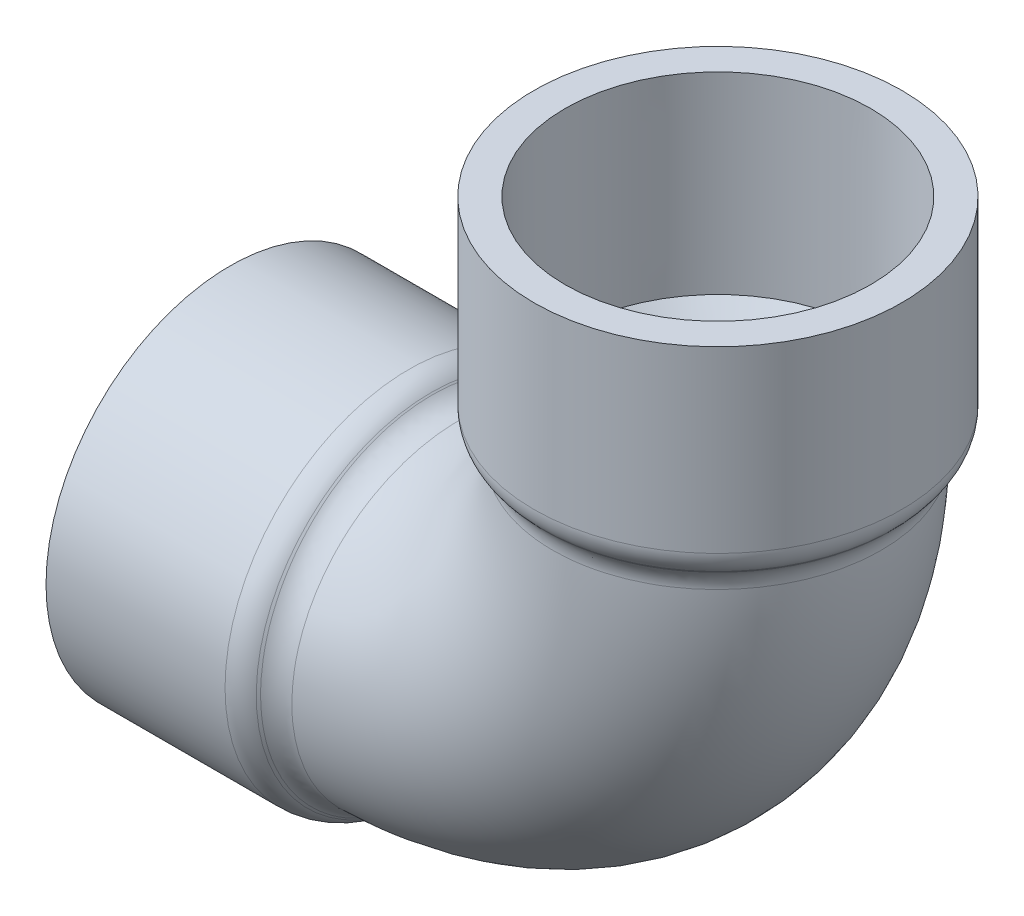
SolidWorks part; units mm, degrees
ref_plane "Front Plane" through (0, 0, 0) normal (0, 0, 1) x (1, 0, 0)
ref_plane "Top Plane" through (0, 0, 0) normal (0, 1, 0) x (1, 0, 0)
ref_plane "Right Plane" through (0, 0, 0) normal (1, 0, 0) x (0, 0, -1)
sketch "Sketch0" plane through (0, 0, 0) normal (0, 0, 1) x (1, 0, 0)
  line L0 (-96.8375, 0) -> (0, 0) construction
  line L1 (0, 0) -> (0, 96.8375) construction
  line L2 (-58.7375, 0) -> (0, 0) construction
  line L3 (0, 0) -> (0, 58.7375) construction
  line L4 (-96.8375, 36.5125) -> (-96.8375, -36.5125) construction
  line L5 (-58.7375, 30.0863) -> (-96.8375, 30.3149) construction
  line L6 (-58.7375, 30.0863) -> (-58.7375, -30.0863) construction
  line L7 (-58.7375, -30.0863) -> (-96.8375, -30.3149) construction
  line L8 (-96.8375, 30.3149) -> (-96.8375, -30.3149) construction
  line L9 (-36.5125, 96.8375) -> (36.5125, 96.8375) construction
  line L10 (-30.3149, 96.8375) -> (30.3149, 96.8375) construction
  line L11 (30.3149, 96.8375) -> (30.0863, 58.7375) construction
  line L12 (30.0863, 58.7375) -> (-30.0863, 58.7375) construction
  line L13 (-30.0863, 58.7375) -> (-30.3149, 96.8375) construction
  line L14 (-58.7375, 26.2509) -> (-58.7375, -26.2509) construction
  line L15 (-58.7375, -26.2509) -> (-58.7375, -32.4485) construction
  line L16 (-96.8375, -30.3149) -> (-96.8375, -36.5125) construction
  line L17 (26.2509, 58.7375) -> (32.4485, 58.7375) construction
  line L18 (-26.2509, 58.7375) -> (26.2509, 58.7375) construction
  line L19 (30.3149, 96.8375) -> (36.5125, 96.8375) construction
  dimension "D1" = 6.1976
  dimension "H" = 96.8375
  dimension "G" = 58.7375
  dimension "M" = 73.025
  dimension "OD A" = 60.6298
  dimension "OD B" = 60.1726
  dimension "ID" = 52.5018
sketch "Sketch1" plane through (0, 0, 0) normal (0, 0, 1) x (1, 0, 0)
  line L0 (-96.8375, 0) -> (0, 0) construction
  line L1 (-96.8375, 0) -> (0, 0) construction
  line L2 (-58.7375, -36.5125) -> (-54.6735, -32.4485)
  line L3 (-96.8375, -36.5125) -> (-58.7375, -36.5125)
  line L4 (-96.8375, -36.5125) -> (-96.8375, -30.3149)
  line L5 (-96.8375, -30.3149) -> (-58.7375, -30.0863)
  line L6 (-58.7375, -36.5125) -> (-58.7375, -30.0863) construction
  line L7 (-54.6735, -32.4485) -> (-54.6735, -26.2509)
  line L8 (-54.6735, -26.2509) -> (-58.7375, -30.0863)
  line L9 (-58.7375, -36.5125) -> (-54.6735, -36.5125) construction
  line L10 (-58.7375, -26.2509) -> (-54.6735, -26.2509) construction
  line L11 (-54.6735, -36.5125) -> (-54.6735, -32.4485) construction
  line L12 (-58.7375, -32.4485) -> (-54.6735, -32.4485) construction
revolve "Revolve1" add sketch "Sketch1" angle 360 about L1
sketch "Sketch2" plane through (0, 0, 0) normal (0, 0, 1) x (1, 0, 0)
  line L0 (30.3149, 96.8375) -> (30.0863, 58.7375)
  line L1 (30.0863, 58.7375) -> (36.5125, 58.7375) construction
  line L2 (36.5125, 58.7375) -> (36.5125, 96.8375)
  line L3 (36.5125, 96.8375) -> (30.3149, 96.8375)
  line L4 (0, 0) -> (0, 96.8375) construction
  line L5 (0, 0) -> (0, 96.8375) construction
  line L6 (30.0863, 58.7375) -> (26.2509, 54.6735)
  line L7 (26.2509, 58.7375) -> (26.2509, 54.6735) construction
  line L8 (36.5125, 58.7375) -> (32.4485, 54.6735)
  line L9 (32.4485, 54.6735) -> (26.2509, 54.6735)
  line L10 (36.5125, 58.7375) -> (36.5125, 54.6735) construction
  line L11 (36.5125, 54.6735) -> (32.4485, 54.6735) construction
  line L12 (32.4485, 58.7375) -> (32.4485, 54.6735) construction
revolve "Revolve2" add sketch "Sketch2" angle 360 about L5
sketch "Sketch3" plane through (-54.6735, 0, 0) normal (1, 0, 0) x (0, 0, -1)
  circle A0 centre (0, 0) radius 26.2509
  circle A1 centre (0, 0) radius 32.4485
sketch "Sketch4" plane through (0, 0, 0) normal (0, 0, 1) x (1, 0, 0)
  line L0 (-96.8375, 0) -> (0, 0) construction
  line L1 (0, 0) -> (0, 96.8375) construction
  line L2 (-96.8375, 0) -> (-54.6735, 0) construction
  line L3 (0, 54.6735) -> (0, 96.8375) construction
  line L4 (-54.6735, -32.4485) -> (-54.6735, 32.4485) construction
  arc A0 (-54.6735, 0) -> (0, 54.6735) centre (-54.6735, 54.6735) ccw
sweep "Sweep1" add profiles "Sketch3" path "Sketch4"
fillet "Fillet1" radius 6.1976 4 edges at (-54.6735, 0, -32.4485) (0, 54.6735, -32.4485) (0, 58.7375, -36.5125) (-58.7375, 0, 36.5125)
equation "\"D1@Fillet1\" = \"D1@Sketch0\""
